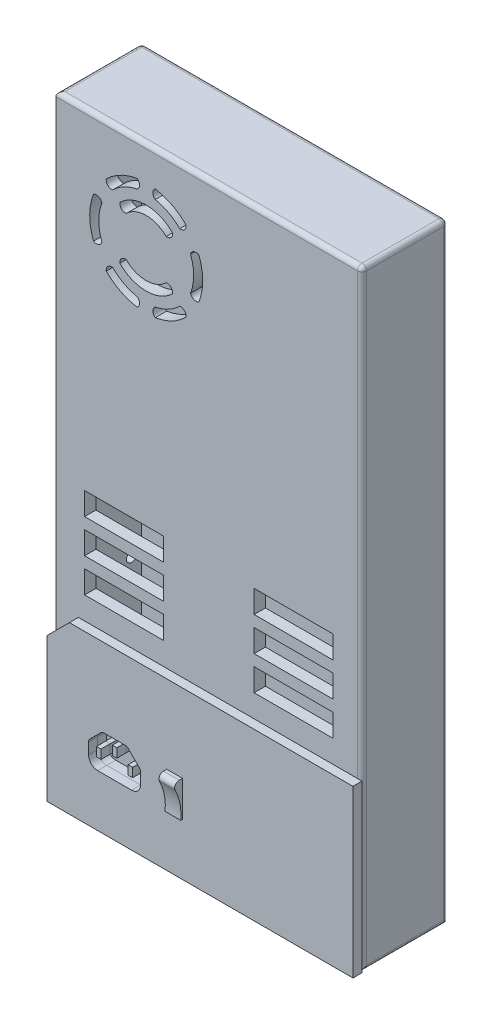
SolidWorks part; units mm, degrees
ref_plane "Front Plane" through (0, 0, 0) normal (0, 0, 1) x (1, 0, 0)
ref_plane "Top Plane" through (0, 0, 0) normal (0, 1, 0) x (1, 0, 0)
ref_plane "Right Plane" through (0, 0, 0) normal (1, 0, 0) x (0, 0, -1)
sketch "Sketch1" plane through (0, 0, 0) normal (0, 1, 0) x (1, 0, 0)
  line L1 (-67.75, -19) -> (67.75, -19)
  line L2 (-67.75, -19) -> (-67.75, 19)
  line L3 (-67.75, 19) -> (67.75, 19)
  line L4 (67.75, -19) -> (67.75, 19)
  line L5 (-67.75, -19) -> (67.75, 19) construction
  line L6 (-67.75, 19) -> (67.75, -19) construction
  point P0 (0, 0)
  dimension "D1" = 135.5
  dimension "D2" = 38
extrude "Boss-Extrude1" add sketch "Sketch1" along normal blind 270
sketch "Sketch3" plane through (0, 0, 19) normal (0, 0, 1) x (1, 0, 0)
  line L0 (67.75, 270) -> (67.75, 0) construction
  line L1 (-67.75, 0) -> (67.75, 0)
  line L2 (-67.75, 0) -> (-67.75, 63.4493)
  line L3 (-57.75, 73.4493) -> (67.75, 73.4493)
  line L4 (67.75, 0) -> (67.75, 73.4493)
  line L5 (-67.75, 63.4493) -> (-57.75, 73.4493)
  point P2 (-67.75, 73.4493)
  dimension "D1" = 73.4493
extrude "Boss-Extrude2" add sketch "Sketch3" along normal blind 4 separate body
shell "Shell2" thickness 5
sketch "Sketch4" plane through (0, 0, 0) normal (0, -1, 0) x (1, 0, 0)
  line L5 (-62.75, 14) -> (62.75, 14)
  line L6 (-62.75, 14) -> (-62.75, -14)
  line L7 (-62.75, -14) -> (62.75, -14)
  line L8 (62.75, 14) -> (62.75, -14)
extrude "Boss-Extrude3" add sketch "Sketch4" against normal blind 5
sketch "Sketch5" plane through (0, 0, 19) normal (0, 0, 1) x (1, 0, 0)
  line L0 (-67.75, 270) -> (67.75, 270) construction
  line L1 (-67.75, 270) -> (-67.75, 0) construction
  line L3 (-27.75, 230) -> (-2.75, 230) construction
  line L4 (-52.75, 230) -> (-48.75, 230) construction
  line L6 (-42.5992, 244.8492) -> (-45.4277, 247.6777) construction
  line L7 (-27.75, 209) -> (-27.75, 205) construction
  line L8 (67.75, 270) -> (67.75, 0) construction
  line L9 (-67.75, 0) -> (67.75, 0) construction
  arc A0 (-51.0738, 239) -> (-51.0738, 221) centre (-27.75, 230) ccw
  arc A1 (-47.365, 237.5) -> (-47.365, 222.5) centre (-27.75, 230) ccw
  arc A2 (-45.4277, 247.6777) -> (-42.5992, 244.8492) centre (-42.9528, 247.3241) ccw
  arc A3 (-31.75, 254.6779) -> (-31.75, 250.6155) centre (-33.2075, 252.6467) cw
  arc A4 (-10.0723, 247.6777) -> (-12.9008, 244.8492) centre (-12.5472, 247.3241) cw
  arc A5 (-23.75, 254.6779) -> (-23.75, 250.6155) centre (-22.2925, 252.6467) ccw
  arc A6 (-45.4277, 212.3223) -> (-42.5992, 215.1508) centre (-42.9528, 212.6759) cw
  arc A7 (-10.0723, 212.3223) -> (-12.9008, 215.1508) centre (-12.5472, 212.6759) ccw
  arc A8 (-23.75, 205.3221) -> (-23.75, 209.3845) centre (-22.2925, 207.3533) cw
  arc A9 (-31.75, 205.3221) -> (-31.75, 209.3845) centre (-33.2075, 207.3533) ccw
  arc A10 (-51.0738, 239) -> (-47.365, 237.5) centre (-49.7817, 236.8598) cw
  arc A11 (-51.0738, 221) -> (-47.365, 222.5) centre (-49.7817, 223.1402) ccw
  arc A12 (-4.4262, 221) -> (-8.135, 222.5) centre (-5.7183, 223.1402) cw
  arc A13 (-4.4262, 239) -> (-8.135, 237.5) centre (-5.7183, 236.8598) ccw
  circle A14 centre (-27.75, 230) radius 21 construction
  circle A15 centre (-27.75, 230) radius 25 construction
  arc A16 (-42.5992, 215.1508) -> (-31.75, 209.3845) centre (-27.75, 230) ccw
  arc A17 (-45.4277, 212.3223) -> (-31.75, 205.3221) centre (-27.75, 230) ccw
  arc A18 (-23.75, 209.3845) -> (-12.9008, 215.1508) centre (-27.75, 230) ccw
  arc A19 (-23.75, 205.3221) -> (-10.0723, 212.3223) centre (-27.75, 230) ccw
  arc A20 (-4.4262, 221) -> (-4.4262, 239) centre (-27.75, 230) ccw
  arc A21 (-8.135, 222.5) -> (-8.135, 237.5) centre (-27.75, 230) ccw
  arc A22 (-10.0723, 247.6777) -> (-23.75, 254.6779) centre (-27.75, 230) ccw
  arc A23 (-12.9008, 244.8492) -> (-23.75, 250.6155) centre (-27.75, 230) ccw
  arc A24 (-31.75, 254.6779) -> (-45.4277, 247.6777) centre (-27.75, 230) ccw
  arc A25 (-31.75, 250.6155) -> (-42.5992, 244.8492) centre (-27.75, 230) ccw
  point P49 (0, 0)
  point P54 (0, 0)
  point P55 (-8.7686, 221.9397)
  dimension "D3" = 50
  dimension "D9" = 2.5
  dimension "D10" = 2.5
  dimension "D11" = 2.5
  dimension "D12" = 4.0624
  dimension "D5" = 2.5
  dimension "D15" = 9.4575
  dimension "D19" = 2.5
  dimension "D23" = 7.9894
  dimension "D24" = 8.4746
  dimension "D1" = 40
  dimension "D2" = 40
  dimension "D6" = 9
  dimension "D7" = 45
  dimension "D8" = 7.5
  dimension "D13" = 25.1508
  dimension "D14" = 36
  dimension "D16" = 10.8492
  dimension "D17" = 7.3492
  dimension "D18" = 5.6461
  dimension "D20" = 19.2028
  dimension "D21" = 2.5
  dimension "D22" = 2.5
  dimension "D25" = 4
  dimension "D4" = 4
extrude "Cut-Extrude1" cut sketch "Sketch5" against normal blind 5
sketch "Sketch6" plane through (0, 0, 19) normal (0, 0, 1) x (1, 0, 0)
  line L0 (-27.75, 230) -> (-16.0827, 241.6673) construction
  line L1 (-27.75, 246.5) -> (-27.75, 213.5) construction
  line L2 (-44.25, 230) -> (-11.25, 230) construction
  arc A0 (-36.5888, 221.1612) -> (-18.9112, 221.1612) centre (-27.75, 230) ccw
  arc A1 (-39.4173, 218.3327) -> (-16.0827, 218.3327) centre (-27.75, 230) ccw
  arc A2 (-16.0827, 241.6673) -> (-18.9112, 238.8388) centre (-18.5576, 241.3137) cw
  arc A3 (-39.4173, 241.6673) -> (-36.5888, 238.8388) centre (-36.9424, 241.3137) ccw
  arc A4 (-16.0827, 218.3327) -> (-18.9112, 221.1612) centre (-18.5576, 218.6863) ccw
  arc A5 (-39.4173, 218.3327) -> (-36.5888, 221.1612) centre (-36.9424, 218.6863) cw
  circle A6 centre (-27.75, 230) radius 12.5 construction
  circle A7 centre (-27.75, 230) radius 16.5 construction
  arc A8 (-18.9112, 238.8388) -> (-36.5888, 238.8388) centre (-27.75, 230) ccw
  arc A9 (-16.0827, 241.6673) -> (-39.4173, 241.6673) centre (-27.75, 230) ccw
  dimension "D1" = 25
  dimension "D4" = 2.5
  dimension "D3" = 45
  dimension "D2" = 4
extrude "Cut-Extrude2" cut sketch "Sketch6" against normal blind 5
sketch "Sketch7" plane through (0, 0, 19) normal (0, 0, 1) x (1, 0, 0)
  line L0 (67.75, 73.4493) -> (-57.75, 73.4493) construction
  line L1 (20, 83.4493) -> (55, 83.4493)
  line L2 (20, 83.4493) -> (20, 93.4493)
  line L3 (20, 93.4493) -> (55, 93.4493)
  line L4 (55, 83.4493) -> (55, 93.4493)
  line L5 (0, 0) -> (0, 166.5792) construction
  line L6 (-67.75, 0) -> (67.75, 0) construction
  line L7 (-20, 93.4493) -> (-55, 93.4493)
  line L8 (-55, 83.4493) -> (-55, 93.4493)
  line L9 (-20, 83.4493) -> (-55, 83.4493)
  line L10 (-20, 83.4493) -> (-20, 93.4493)
  line L11 (-20, 108.4493) -> (-55, 108.4493)
  line L12 (-55, 98.4493) -> (-55, 108.4493)
  line L13 (-20, 98.4493) -> (-55, 98.4493)
  line L14 (-20, 98.4493) -> (-20, 108.4493)
  line L15 (20, 98.4493) -> (20, 108.4493)
  line L16 (20, 98.4493) -> (55, 98.4493)
  line L17 (55, 98.4493) -> (55, 108.4493)
  line L18 (20, 108.4493) -> (55, 108.4493)
  line L19 (-20, 123.4493) -> (-55, 123.4493)
  line L20 (-55, 113.4493) -> (-55, 123.4493)
  line L21 (-20, 113.4493) -> (-55, 113.4493)
  line L22 (-20, 113.4493) -> (-20, 123.4493)
  line L23 (20, 113.4493) -> (20, 123.4493)
  line L24 (20, 113.4493) -> (55, 113.4493)
  line L25 (55, 113.4493) -> (55, 123.4493)
  line L26 (20, 123.4493) -> (55, 123.4493)
  dimension "D1" = 20
  dimension "D2" = 35
  dimension "D3" = 10
  dimension "D4" = 10
  dimension "D6" = 81.8727
  dimension "D5" = 3
extrude "Cut-Extrude3" cut sketch "Sketch7" against normal blind 5
fillet "Fillet1" radius 2 9 edges at (67.75, 135, 19) (67.75, 135, -19) (67.75, 0, 0) (-67.75, 135, -19) (0, 270, 19) (-67.75, 270, 0) (0, 270, -19) (67.75, 270, 0) (62.75, 135, 14)
sketch "Sketch8" plane through (0, 0, 23) normal (0, 0, 1) x (1, 0, 0)
  line L0 (-67.75, 0) -> (67.75, 0) construction
  line L1 (-45.25, 23) -> (-30.25, 23)
  line L2 (-49.25, 27) -> (-49.25, 31.9716)
  line L3 (-42.4216, 38.8) -> (-33.0784, 38.8)
  line L4 (-26.25, 27) -> (-26.25, 31.9716)
  line L5 (-67.75, 63.4493) -> (-67.75, 0) construction
  line L6 (-37.75, 30) -> (-37.75, 25.4236) construction
  line L7 (-38.75, 32) -> (-36.75, 32)
  line L8 (-38.75, 32) -> (-38.75, 36)
  line L9 (-38.75, 36) -> (-36.75, 36)
  line L10 (-36.75, 32) -> (-36.75, 36)
  line L11 (-38.75, 32) -> (-36.75, 36) construction
  line L12 (-38.75, 36) -> (-36.75, 32) construction
  line L13 (-45.75, 28) -> (-43.75, 28)
  line L14 (-45.75, 28) -> (-45.75, 32)
  line L15 (-45.75, 32) -> (-43.75, 32)
  line L16 (-43.75, 28) -> (-43.75, 32)
  line L17 (-45.75, 28) -> (-43.75, 32) construction
  line L18 (-45.75, 32) -> (-43.75, 28) construction
  line L23 (-29.75, 32) -> (-31.75, 32)
  line L24 (-31.75, 28) -> (-31.75, 32)
  line L25 (-29.75, 28) -> (-31.75, 28)
  line L26 (-29.75, 28) -> (-29.75, 32)
  line L27 (-48.6642, 33.3858) -> (-43.8358, 38.2142)
  line L28 (-31.6642, 38.2142) -> (-26.8358, 33.3858)
  arc A0 (-26.8358, 33.3858) -> (-26.25, 31.9716) centre (-28.25, 31.9716) cw
  arc A1 (-31.6642, 38.2142) -> (-33.0784, 38.8) centre (-33.0784, 36.8) ccw
  arc A2 (-48.6642, 33.3858) -> (-49.25, 31.9716) centre (-47.25, 31.9716) ccw
  arc A3 (-43.8358, 38.2142) -> (-42.4216, 38.8) centre (-42.4216, 36.8) cw
  arc A4 (-30.25, 23) -> (-26.25, 27) centre (-30.25, 27) ccw
  arc A5 (-45.25, 23) -> (-49.25, 27) centre (-45.25, 27) cw
  point P0 (-37.75, 30)
  point P1 (-26.25, 38.8)
  point P3 (-49.25, 38.8)
  point P11 (-37.75, 34)
  point P16 (-44.75, 30)
  point P33 (-26.25, 32.8)
  point P36 (-32.25, 38.8)
  point P39 (-49.25, 32.8)
  point P42 (-43.25, 38.8)
  point P45 (-26.25, 23)
  point P48 (-49.25, 23)
  dimension "D8" = 2
  dimension "D11" = 4
  dimension "D1" = 30
  dimension "D2" = 30
  dimension "D3" = 23
  dimension "D4" = 15.8
  dimension "D5" = 18.5
  dimension "D6" = 23
  dimension "D7" = 7
  dimension "D9" = 4
  dimension "D10" = 2
  dimension "D12" = 2
  dimension "D13" = 4
  dimension "D15" = 4
extrude "Cut-Extrude4" cut sketch "Sketch8" against normal blind 8
sketch "Sketch9" plane through (0, 0, 23) normal (0, 0, 1) x (1, 0, 0)
  line L0 (-14.6694, 38.8) -> (-7.7136, 38.8)
  line L3 (-14.6694, 23) -> (-7.7136, 23)
  line L5 (-7.7136, 23) -> (-7.7136, 38.8)
  line L6 (-14.6694, 38.8) -> (-14.6694, 23)
  line L7 (-49.25, 31.9716) -> (-49.25, 27) construction
  line L8 (-45.25, 23) -> (-30.25, 23) construction
  dimension "D1" = 34.5806
  dimension "D2" = 41.5364
  dimension "D3" = 15.8
extrude "Boss-Extrude5" add sketch "Sketch9" along normal blind 5 separate body
sketch "Sketch10" plane through (-7.7136, 0, 0) normal (1, 0, 0) x (0, 0, -1)
  line L0 (-28, 23) -> (-23, 23) construction
  line L1 (-23, 0) -> (-23, 73.4493) construction
  line L2 (-28, 38.8) -> (-28, 23)
  line L3 (-28, 23) -> (-23.7, 23)
  arc A0 (-28, 38.8) -> (-23.7, 23) centre (-47.6185, 24.9756) cw
  dimension "D1" = 24
  dimension "D2" = 0.7
sketch "Sketch11" plane through (-67.75, 0, 0) normal (-1, 0, 0) x (0, 0, 1)
  line L3 (-17, 0) -> (19, 0) construction
  line L4 (-19, 0) -> (-19, 268) construction
  circle A0 centre (-9.5, 230) radius 2.25
  circle A1 centre (-9.5, 80) radius 2.25
  point P4 (-11.75, 230)
  point P9 (-11.75, 80)
  dimension "D1" = 4.5
  dimension "D4" = 4.5
  dimension "D5" = 7.25
  dimension "D2" = 7.25
  dimension "D3" = 230
  dimension "D6" = 80
extrude "Cut-Extrude6" cut sketch "Sketch11" against normal blind 5
extrude "Cut-Extrude7" cut sketch "Sketch10" against normal through all contours A0 L3 L2
fillet "Fillet2" radius 2 1 edges at (-11.1915, 38.8, 28)
